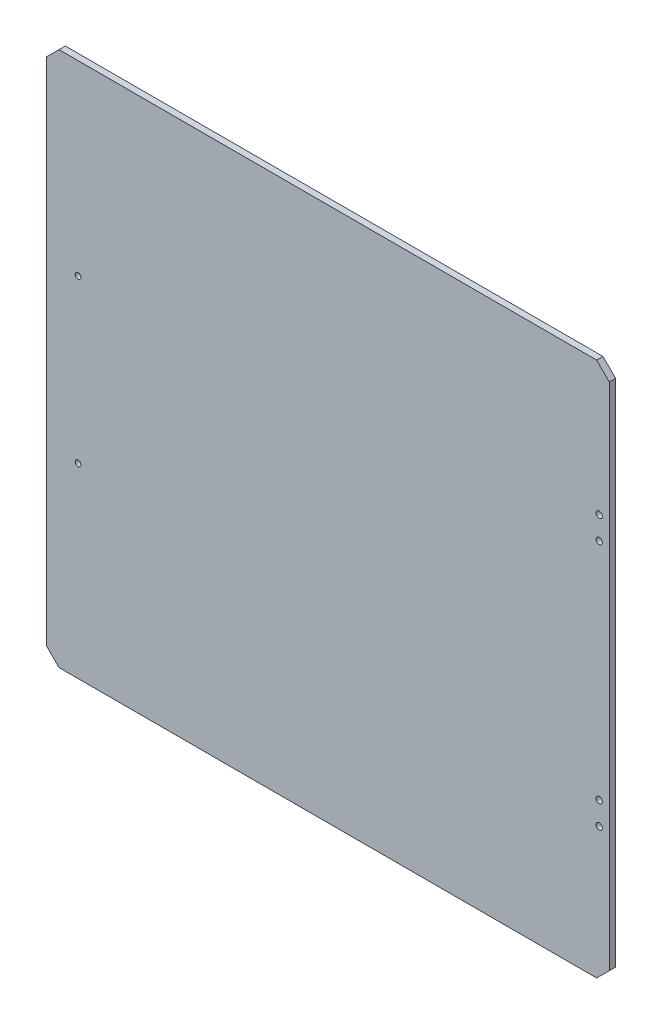
SolidWorks part; units mm, degrees
material "Acrilico (impatto medio-alto)"
ref_plane "Piano frontale" through (0, 0, 0) normal (0, 0, 1) x (1, 0, 0)
ref_plane "Piano superiore" through (0, 0, 0) normal (0, 1, 0) x (1, 0, 0)
ref_plane "Piano destro" through (0, 0, 0) normal (1, 0, 0) x (0, 0, -1)
sketch "Schizzo1" plane through (0, 0, 0) normal (0, 0, 1) x (1, 0, 0)
  line L0 (-222, 201) -> (-212, 211)
  line L1 (212, -211) -> (-212, -211)
  line L2 (222, -201) -> (222, 201)
  line L3 (212, 211) -> (-212, 211)
  line L4 (-222, -201) -> (-222, 201)
  line L5 (222, -211) -> (-222, 211) construction
  line L6 (222, 211) -> (-222, -211) construction
  line L7 (222, 201) -> (212, 211)
  line L8 (212, -211) -> (222, -201)
  line L9 (-212, -211) -> (-222, -201)
  line L10 (214, 237.3502) -> (214, -235.7038) construction
  line L11 (-222, 0) -> (222, 0) construction
  circle A0 centre (214, 106.4404) radius 2.5
  circle A1 centre (214, 88.4404) radius 2.5
  circle A2 centre (214, -88.4404) radius 2.5
  circle A3 centre (214, -106.4404) radius 2.5
  circle A5 centre (-197, 64) radius 2.25
  circle A6 centre (-197, -64) radius 2.25
  point P0 (0, 0)
  dimension "D9" = 5
  dimension "D12" = 4.5
  dimension "D1" = 444
  dimension "D2" = 422
  dimension "D3" = 8
  dimension "D4" = 18
  dimension "D10" = 25
  dimension "D11" = 64
extrude "Estrusione-Estrusione1" add sketch "Schizzo1" along normal blind 5
